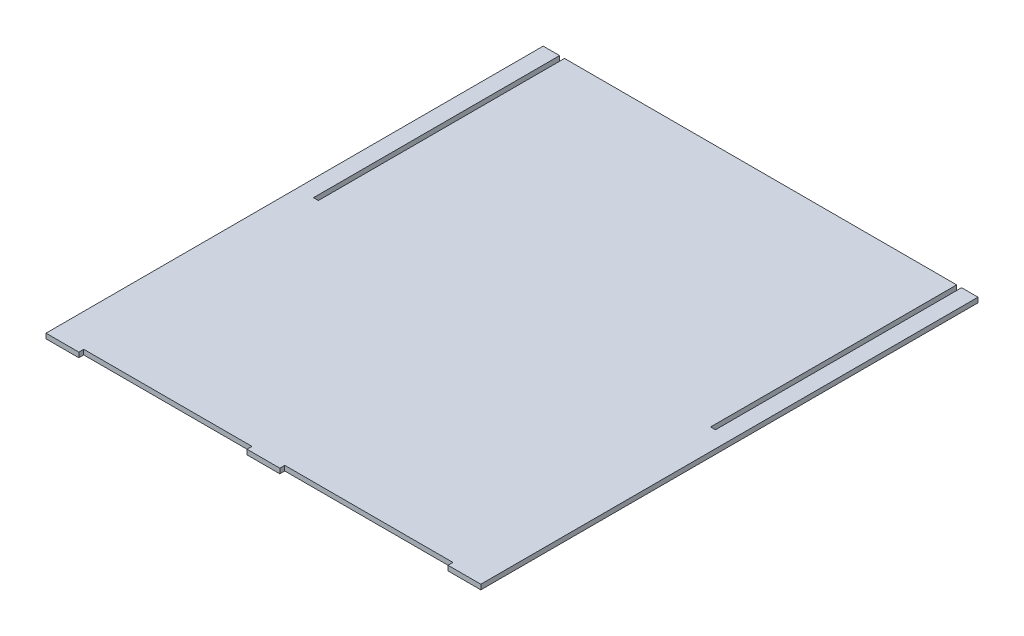
SolidWorks part; units mm, degrees
ref_plane "Front Plane" through (0, 0, 0) normal (0, 0, 1) x (1, 0, 0)
ref_plane "Top Plane" through (0, 0, 0) normal (0, 1, 0) x (1, 0, 0)
ref_plane "Right Plane" through (0, 0, 0) normal (1, 0, 0) x (0, 0, -1)
sketch "Sketch1" plane through (0, 0, 0) normal (0, 1, 0) x (1, 0, 0)
  line L0 (-530, 0) -> (-490, 0)
  line L2 (0, 0) -> (0, 606)
  line L3 (0, 606) -> (-530, 606)
  line L4 (-530, 0) -> (-530, 606)
  line L5 (-490, 0) -> (-490, 6)
  line L6 (0, 0) -> (-40, 0)
  line L7 (-40, 0) -> (-40, 6)
  line L8 (-40, 6) -> (-245, 6)
  line L9 (-245, 6) -> (-245, 0)
  line L10 (-245, 0) -> (-285, 0)
  line L11 (-285, 0) -> (-285, 6)
  line L12 (-285, 6) -> (-490, 6)
  dimension "D1" = 530
  dimension "D2" = 606
  dimension "D3" = 40
  dimension "D4" = 6
extrude "Boss-Extrude1" add sketch "Sketch1" along normal blind 6 contours L4 L3 L2 L6 L7 L8 L9 L10 L11 L12 L5 L0
sketch "Sketch2" plane through (0, 6, 0) normal (0, 1, 0) x (1, 0, 0)
  line L1 (-20, 606) -> (-26, 606)
  line L2 (-20, 606) -> (-20, 306)
  line L3 (-20, 306) -> (-26, 306)
  line L4 (-26, 606) -> (-26, 306)
  line L6 (0, 0) -> (0, 606) construction
  line L7 (0, 606) -> (-530, 606) construction
  dimension "D1" = 6
  dimension "D2" = 20
  dimension "D3" = 300
extrude "Cut-Extrude1" cut sketch "Sketch2" against normal blind 6
pattern_linear "LPattern1" count 2 spacing 484 along (-1, 0, 0) of "Cut-Extrude1"
